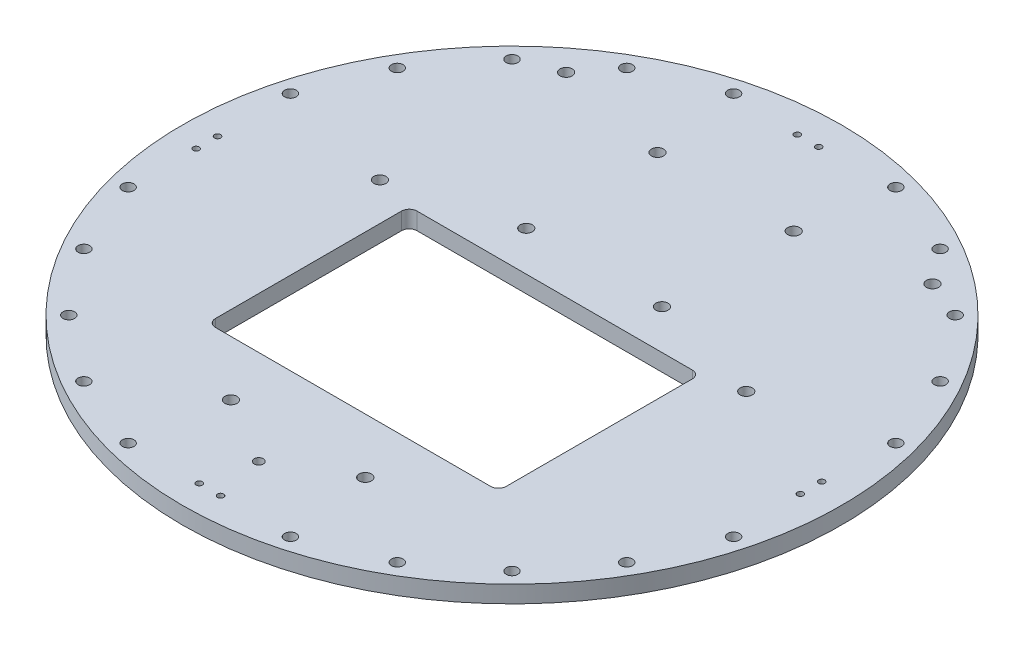
SolidWorks part; units mm, degrees
material "Acrylique (impact moyen-haut)"
ref_plane "Plan de face" through (0, 0, 0) normal (0, 0, 1) x (1, 0, 0)
ref_plane "Plan de dessus" through (0, 0, 0) normal (0, 1, 0) x (1, 0, 0)
ref_plane "Plan de droite" through (0, 0, 0) normal (1, 0, 0) x (0, 0, -1)
sketch "Esquisse1" plane through (0, 0, 0) normal (0, 1, 0) x (1, 0, 0)
  circle A0 centre (0, 0) radius 107.95
  dimension "D1" = 215.9
extrude "Boss.-Extru.1" add sketch "Esquisse1" along normal blind 5.588
sketch "Esquisse2" plane through (0, 5.588, 0) normal (0, 1, 0) x (1, 0, 0)
  line L0 (0, 0) -> (0, 102.6583) construction
  circle A1 centre (26.5699, 99.1603) radius 1.905
  circle A2 centre (51.3292, 88.9047) radius 1.905
  circle A3 centre (72.5904, 72.5904) radius 1.905
  circle A4 centre (88.9047, 51.3292) radius 1.905
  circle A5 centre (99.1603, 26.5699) radius 1.905
  circle A7 centre (99.1603, -26.5699) radius 1.905
  circle A8 centre (88.9047, -51.3292) radius 1.905
  circle A9 centre (72.5904, -72.5904) radius 1.905
  circle A10 centre (51.3292, -88.9047) radius 1.905
  circle A11 centre (26.5699, -99.1603) radius 1.905
  circle A13 centre (-26.5699, -99.1603) radius 1.905
  circle A14 centre (-51.3292, -88.9047) radius 1.905
  circle A15 centre (-72.5904, -72.5904) radius 1.905
  circle A16 centre (-88.9047, -51.3292) radius 1.905
  circle A17 centre (-99.1603, -26.5699) radius 1.905
  circle A19 centre (-99.1603, 26.5699) radius 1.905
  circle A20 centre (-88.9047, 51.3292) radius 1.905
  circle A21 centre (-72.5904, 72.5904) radius 1.905
  circle A22 centre (-51.3292, 88.9047) radius 1.905
  circle A23 centre (-26.5699, 99.1603) radius 1.905
  point P53 (0, 0)
  dimension "D1" = 102.6583
extrude "Enlèv. mat.-Extru.1" cut sketch "Esquisse2" against normal blind 5.588
sketch "Esquisse3" plane through (0, 5.588, 0) normal (0, 1, 0) x (1, 0, 0)
  line L0 (0, -107.95) -> (0, -52.07) construction
  line L1 (-45.085, -52.07) -> (45.085, -52.07)
  line L2 (47.625, -49.53) -> (47.625, 11.43)
  line L3 (45.085, 13.97) -> (-45.085, 13.97)
  line L4 (-47.625, 11.43) -> (-47.625, -49.53)
  circle A0 centre (0, 0) radius 107.95 construction
  arc A1 (-45.085, -52.07) -> (-47.625, -49.53) centre (-45.085, -49.53) cw
  arc A2 (45.085, -52.07) -> (47.625, -49.53) centre (45.085, -49.53) ccw
  arc A3 (47.625, 11.43) -> (45.085, 13.97) centre (45.085, 11.43) ccw
  arc A4 (-45.085, 13.97) -> (-47.625, 11.43) centre (-45.085, 11.43) ccw
  point P12 (0, -52.07)
  point P14 (-47.625, -52.07)
  point P17 (47.625, -52.07)
  point P20 (47.625, 13.97)
  dimension "D4" = 2.54
  dimension "D1" = 55.88
  dimension "D2" = 95.25
  dimension "D3" = 66.04
extrude "Enlèv. mat.-Extru.2" cut sketch "Esquisse3" against normal blind 5.588
sketch "Esquisse5" plane through (0, 5.588, 0) normal (0, 1, 0) x (1, 0, 0)
  line L0 (0, -107.95) -> (0, -98.95) construction
  line L1 (0, -98.95) -> (-3.5, -98.95) construction
  circle A0 centre (0, 0) radius 107.95 construction
  circle A1 centre (-3.5, -98.95) radius 1
  circle A2 centre (3.5, -98.95) radius 1
  circle A3 centre (-98.95, 2.5) radius 1
  circle A4 centre (-98.95, -4.5) radius 1
  circle A5 centre (2.5, 97.95) radius 1
  circle A6 centre (-4.5, 97.95) radius 1
  circle A7 centre (97.95, -3.5) radius 1
  circle A8 centre (97.95, 3.5) radius 1
  point P25 (-0.5, -0.5)
  dimension "D3" = 2
  dimension "D1" = 9
  dimension "D2" = 3.5
  dimension "D4" = 4
extrude "Enlèv. mat.-Extru.3" cut sketch "Esquisse5" against normal through all
sketch "Esquisse6" plane through (0, 5.588, 0) normal (0, 1, 0) x (1, 0, 0)
  line L0 (0, -52.07) -> (0, -70.07) construction
  line L1 (-45.085, -52.07) -> (45.085, -52.07) construction
  line L2 (0, -70.07) -> (-22, -70.07) construction
  line L3 (0, -70.07) -> (22, -70.07) construction
  line L4 (0, 13.97) -> (0, 69.97) construction
  line L5 (0, 69.97) -> (-22.3, 69.97) construction
  line L6 (45.085, 13.97) -> (-45.085, 13.97) construction
  line L9 (-22.3, 69.97) -> (-22.3, 26.97) construction
  line L10 (-22.3, 26.97) -> (58.5731, 26.97) construction
  circle A0 centre (-22, -70.07) radius 2
  circle A1 centre (22, -70.07) radius 2
  circle A3 centre (-22.3, 69.97) radius 2
  circle A4 centre (22.3, 69.97) radius 2
  circle A7 centre (-22.3, 26.97) radius 2
  circle A8 centre (22.15, 26.97) radius 2
  dimension "D3" = 4
  dimension "D5" = 4
  dimension "D8" = 4
  dimension "D13" = 22.15
  dimension "D1" = 18
  dimension "D2" = 22
  dimension "D4" = 22
  dimension "D6" = 22.3
  dimension "D7" = 56
  dimension "D12" = 43
extrude "Enlèv. mat.-Extru.4" cut sketch "Esquisse6" against normal through all
sketch "Esquisse8" plane through (0, 5.588, 0) normal (0, 1, 0) x (1, 0, 0)
  line L0 (0, -107.95) -> (0, -82.95) construction
  circle A0 centre (0, 0) radius 107.95 construction
  circle A1 centre (0, -82.95) radius 1.5
  dimension "D2" = 3
  dimension "D1" = 25
extrude "Enlèv. mat.-Extru.6" cut sketch "Esquisse8" against normal through all
sketch "Esquisse10" plane through (0, 5.588, 0) normal (0, 1, 0) x (1, 0, 0)
  line L0 (0, 13.97) -> (0, 16.73) construction
  line L1 (45.085, 13.97) -> (-45.085, 13.97) construction
  line L2 (0, 16.73) -> (-60, 16.73) construction
  line L3 (-60, 16.73) -> (-60, 77.73) construction
  circle A0 centre (-60, 16.73) radius 2
  circle A1 centre (60, 16.73) radius 2
  circle A3 centre (-60, 77.73) radius 2
  circle A4 centre (60, 77.73) radius 2
  dimension "D3" = 4
  dimension "D4" = 61
  dimension "D5" = 4
  dimension "D1" = 2.76
  dimension "D2" = 60
extrude "Enlèv. mat.-Extru.7" cut sketch "Esquisse10" against normal through all
